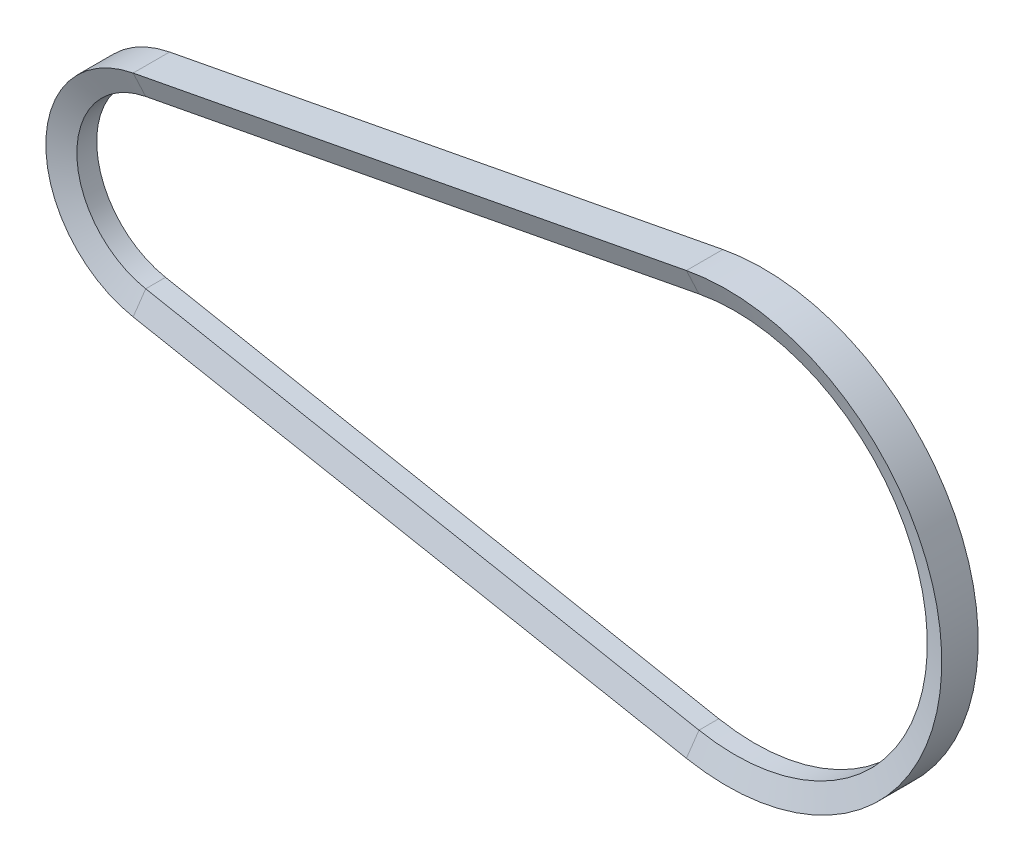
SolidWorks part; units mm, degrees
ref_plane "Front Plane" through (0, 0, 0) normal (0, 0, 1) x (1, 0, 0)
ref_plane "Top Plane" through (0, 0, 0) normal (0, 1, 0) x (1, 0, 0)
ref_plane "Right Plane" through (0, 0, 0) normal (1, 0, 0) x (0, 0, -1)
sketch "Sketch1" plane through (0, 0, 0) normal (0, 0, 1) x (1, 0, 0)
  line L0 (0, 0) -> (200, 0) construction
  line L1 (-7.0312, 36.8349) -> (185.9375, 73.6698)
  line L2 (-7.0312, -36.8349) -> (185.9375, -73.6698)
  arc A0 (-7.0312, 36.8349) -> (-7.0312, -36.8349) centre (0, 0) ccw
  arc A1 (185.9375, -73.6698) -> (185.9375, 73.6698) centre (200, 0) ccw
  dimension "D1" = 75
  dimension "D2" = 150
  dimension "D3" = 200
ref_plane "Plane1" through (-7.0312, 36.8349, 0) normal (0.9823, 0.1875, 0) x (0, 0, -1)
sketch "Sketch2" plane through (-7.0312, 36.8349, 0) normal (0.9823, 0.1875, 0) x (0, 0, -1)
  line L0 (6.35, 0) -> (-6.35, 0)
  line L1 (-6.35, 0) -> (-3.461, -7.9375)
  line L2 (-3.461, -7.9375) -> (3.461, -7.9375)
  line L3 (0, 0) -> (0, -7.9375) construction
  line L5 (6.35, 0) -> (3.461, -7.9375)
  dimension "D1" = 6.35
  dimension "D2" = 20
  dimension "D3" = 7.9375
sweep "Sweep1" add profiles "Sketch2" path "Sketch1"
